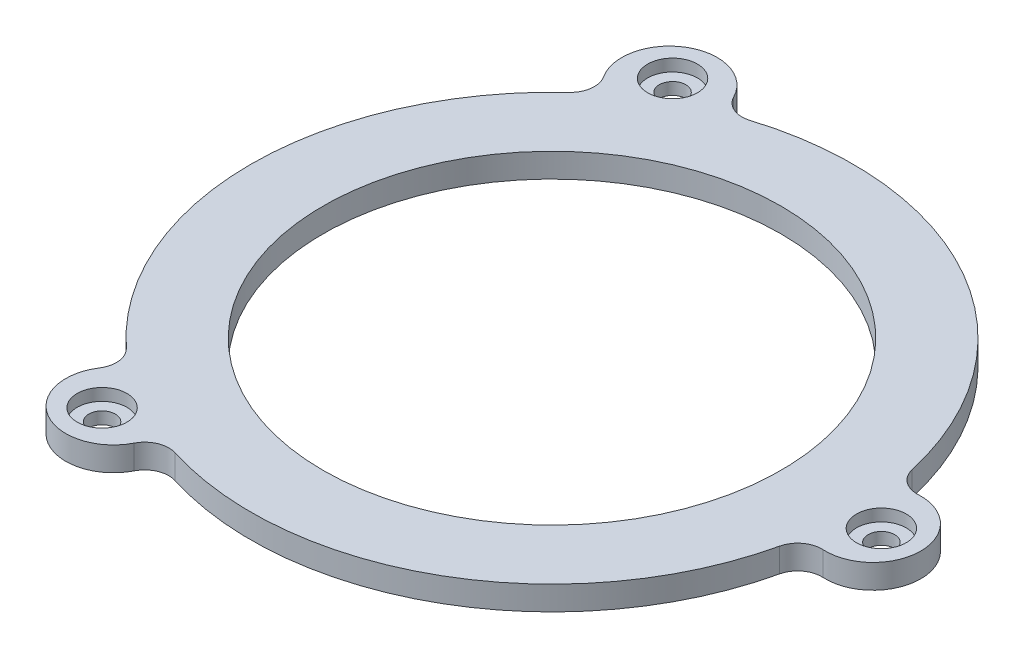
SolidWorks part; units mm, degrees
ref_plane "Front Plane" through (0, 0, 0) normal (0, 0, 1) x (1, 0, 0)
ref_plane "Top Plane" through (0, 0, 0) normal (0, 1, 0) x (1, 0, 0)
ref_plane "Right Plane" through (0, 0, 0) normal (1, 0, 0) x (0, 0, -1)
sketch "Sketch1" plane through (0, 0, 0) normal (0, 1, 0) x (1, 0, 0)
  circle A0 centre (0, 0) radius 28.5
  circle A1 centre (0, 0) radius 37.5
  dimension "D1" = 57
  dimension "D2" = 75
extrude "Boss-Extrude1" add sketch "Sketch1" along normal blind 3
sketch "Sketch3" plane through (0, 3, 0) normal (0, 1, 0) x (1, 0, 0)
  line L1 (0, 0) -> (44, 0) construction
  line L2 (0, 0) -> (37.1351, -5.219) construction
  line L3 (0, 0) -> (37.1351, 5.219) construction
  arc A1 (37.1351, 5.219) -> (37.1351, -5.219) centre (39.9644, 0) cw
  circle A4 centre (0, 0) radius 37.5 construction
  arc A5 (37.1351, 5.219) -> (37.1351, -5.219) centre (0, 0) cw
  arc A11 (-14.0477, -34.7694) -> (-23.0873, -29.5504) centre (-19.9822, -34.6102) cw
  arc A12 (-14.0477, -34.7694) -> (-23.0873, -29.5504) centre (0, 0) cw
  arc A13 (-23.0873, 29.5504) -> (-14.0477, 34.7694) centre (-19.9822, 34.6102) cw
  arc A14 (-23.0873, 29.5504) -> (-14.0477, 34.7694) centre (0, 0) cw
  point P17 (0, 0)
  dimension "D1" = 8
  dimension "D2" = 8
  dimension "D3" = 3
extrude "Boss-Extrude2" add sketch "Sketch3" against normal blind 3
sketch "Sketch6" plane through (0, 3, 0) normal (0, 1, 0) x (1, 0, 0)
  line L0 (0, 0) -> (41, 0) construction
  circle A0 centre (41, 0) radius 1.65
  circle A3 centre (-20.5, -35.507) radius 1.65
  circle A4 centre (-20.5, 35.507) radius 1.65
  point P11 (0, 0)
  dimension "D1" = 3.3
  dimension "D2" = 41
extrude "Cut-Extrude2" cut sketch "Sketch6" against normal blind 10
sketch "Sketch7" plane through (0, 3, 0) normal (0, 1, 0) x (1, 0, 0)
  circle A0 centre (41, 0) radius 3.1
  circle A5 centre (-20.5, -35.507) radius 3.1
  circle A6 centre (-20.5, 35.507) radius 3.1
  point P10 (1, 0.5774)
  point P11 (0.75, 0.433)
  point P16 (0, 0)
  dimension "D1" = 6.2
  dimension "D3" = 3
extrude "Cut-Extrude3" cut sketch "Sketch7" against normal blind 1.5
fillet "Fillet1" radius 3 6 edges at (37.1351, 1.5, 5.219) (37.1351, 1.5, -5.219) (-23.0873, 1.5, 29.5504) (-14.0477, 1.5, 34.7694) (-14.0477, 1.5, -34.7694) (-23.0873, 1.5, -29.5504)
